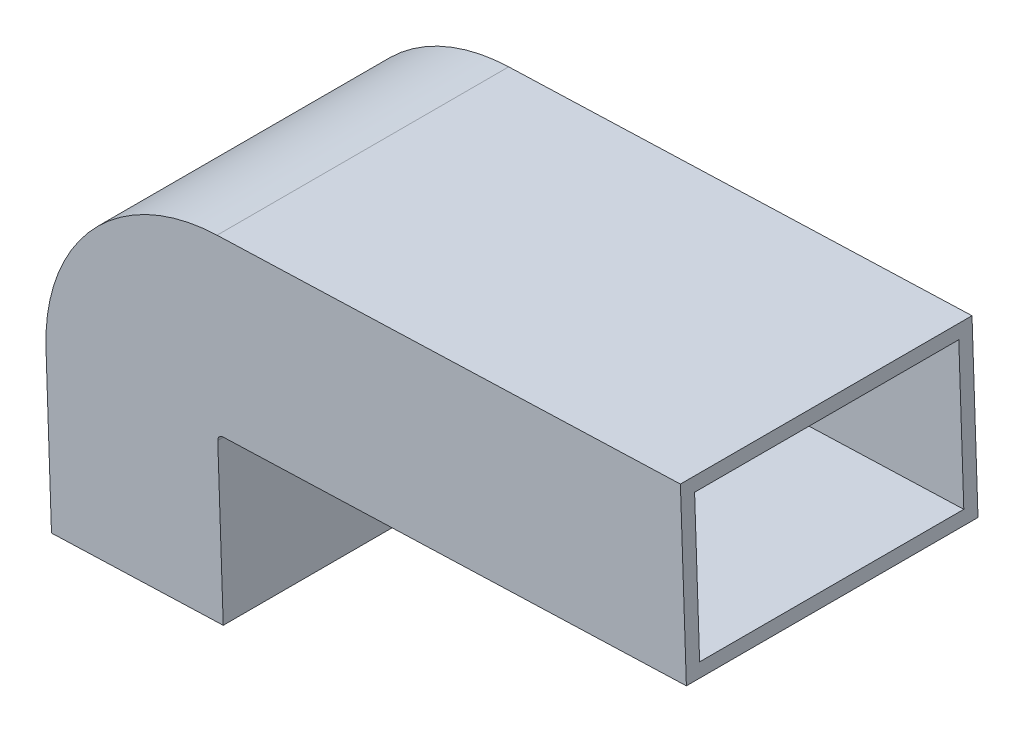
SolidWorks part; units mm, degrees
ref_plane "Front Plane" through (0, 0, 0) normal (0, 0, 1) x (1, 0, 0)
ref_plane "Top Plane" through (0, 0, 0) normal (0, 1, 0) x (1, 0, 0)
ref_plane "Right Plane" through (0, 0, 0) normal (1, 0, 0) x (0, 0, -1)
sketch "Sketch1" plane through (0, 0, 0) normal (0, 0, 1) x (1, 0, 0)
  line L0 (-43.0353, -24.1718) -> (-44.2347, 10.2506)
  line L1 (-24.9432, 30.9349) -> (76.4263, 34.4669)
  arc A0 (-44.2347, 10.2506) -> (-24.9432, 30.9349) centre (-24.2468, 10.947) cw
  dimension "D1" = 20
ref_plane "Plane1" through (76.4263, 34.4669, 0) normal (0.9994, 0.0348, 0) x (0, 0, -1)
sketch "Sketch2" plane through (76.4263, 34.4669, 0) normal (0.9994, 0.0348, 0) x (0, 0, -1)
  line L0 (0, 0) -> (0, -20) construction
  line L1 (-28.9001, 15.8013) -> (28.9001, 15.8013)
  line L2 (-28.9001, 15.8013) -> (-28.9001, -15.8013)
  line L3 (-28.9001, -15.8013) -> (28.9001, -15.8013)
  line L4 (28.9001, 15.8013) -> (28.9001, -15.8013)
  line L5 (-28.9001, 15.8013) -> (28.9001, -15.8013) construction
  line L6 (-28.9001, -15.8013) -> (28.9001, 15.8013) construction
  point P0 (0, 0)
sweep "Sweep-Thin1" add profiles "Sketch2" path "Sketch1" parameters "D1"=3
